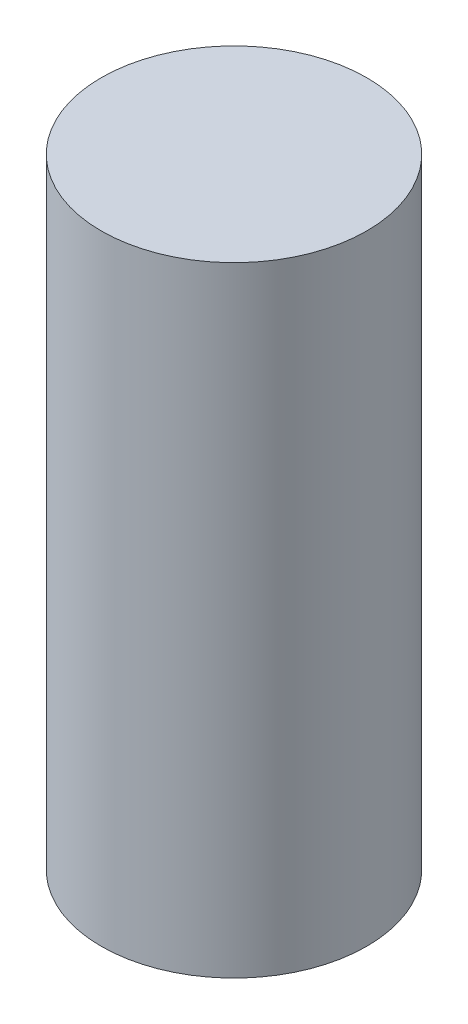
SolidWorks part; units mm, degrees
ref_plane "Front Plane" through (0, 0, 0) normal (0, 0, 1) x (1, 0, 0)
ref_plane "Top Plane" through (0, 0, 0) normal (0, 1, 0) x (1, 0, 0)
ref_plane "Right Plane" through (0, 0, 0) normal (1, 0, 0) x (0, 0, -1)
other "Configuration Table"
sketch "Sketch1" plane through (0, 0, 0) normal (0, 1, 0) x (1, 0, 0)
  circle A0 centre (650, 50) radius 6
extrude "PACK_ayar_mil_2" add sketch "Sketch1" along normal blind 28 from offset 12 separate body
